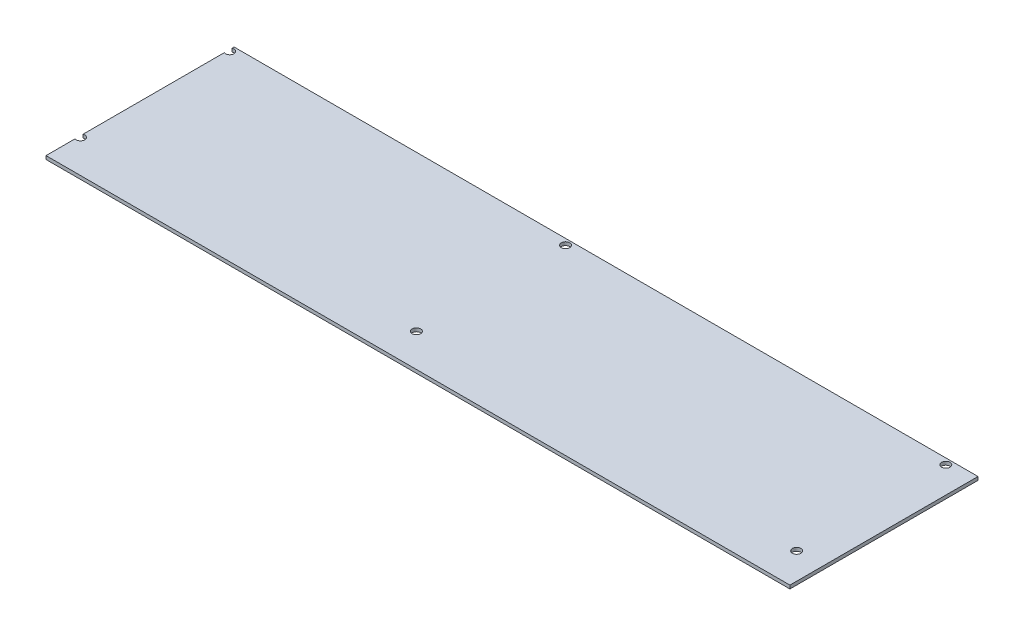
SolidWorks part; units mm, degrees
material "PC High Viscosity"
ref_plane "Front Plane" through (0, 0, 0) normal (0, 0, 1) x (1, 0, 0)
ref_plane "Top Plane" through (0, 0, 0) normal (0, 1, 0) x (1, 0, 0)
ref_plane "Right Plane" through (0, 0, 0) normal (1, 0, 0) x (0, 0, -1)
sketch "Sketch1" plane through (0, 0, 0) normal (0, 1, 0) x (1, 0, 0)
  line L1 (0, 0) -> (696.9125, 0)
  line L2 (0, 0) -> (0, -176.2125)
  line L3 (0, -176.2125) -> (696.9125, -176.2125)
  line L4 (696.9125, 0) -> (696.9125, -176.2125)
  dimension "D1" = 696.9125
  dimension "D2" = 176.2125
extrude "Boss-Extrude1" add sketch "Sketch1" along normal blind 3.175
extrude "Cut-Extrude1" cut sketch "Sketch2" against normal through all and the other way through all
sketch "Sketch2" plane through (312.1415, 3.175, 70.3995) normal (0, 1, 0) x (1, 0, 0)
  line L0 (360.1647, 83.8933) -> (360.1647, -93.9067) construction
  line L6 (347.4647, -5.0067) -> (371.2772, -5.0067) construction
  line L8 (3.9083, 83.8933) -> (3.9083, -93.9067) construction
  line L11 (-310.6722, 83.8933) -> (-310.6722, -93.9067) construction
  circle A0 centre (360.1647, 64.8433) radius 3.9688
  circle A1 centre (360.1647, -74.8567) radius 3.9688
  circle A3 centre (3.9083, 64.8433) radius 3.9687
  circle A4 centre (-310.6722, 64.8433) radius 3.9688
  circle A5 centre (3.9083, -74.8567) radius 3.9687
  circle A6 centre (-310.6722, -74.8567) radius 3.9688
